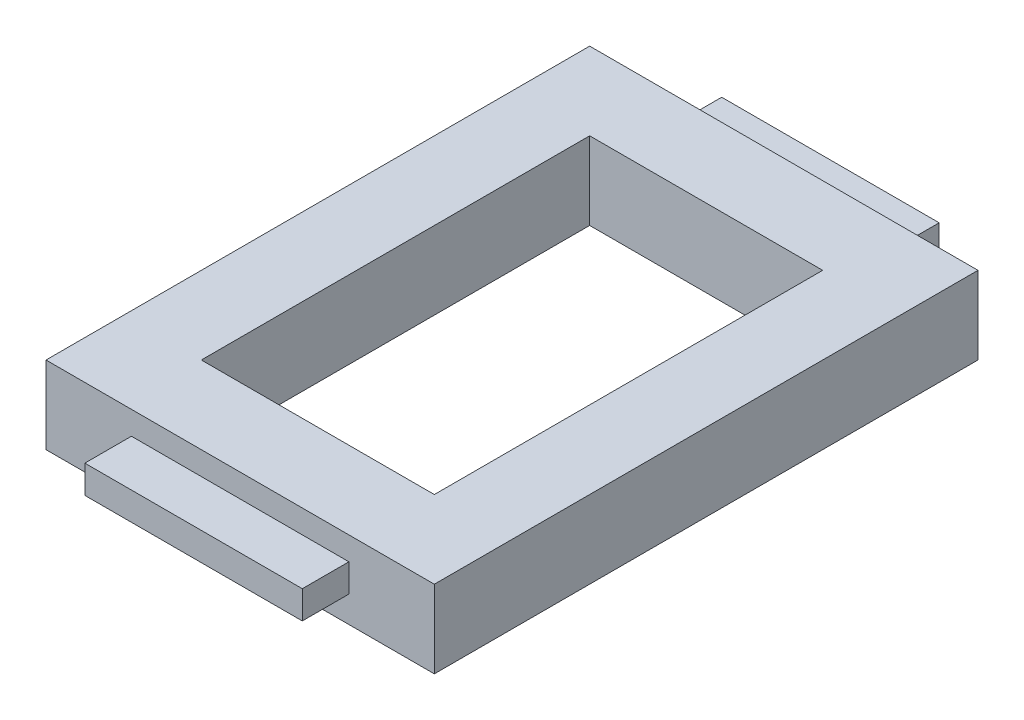
SolidWorks part; units mm, degrees
ref_plane "Front Plane" through (0, 0, 0) normal (0, 0, 1) x (1, 0, 0)
ref_plane "Top Plane" through (0, 0, 0) normal (0, 1, 0) x (1, 0, 0)
ref_plane "Right Plane" through (0, 0, 0) normal (1, 0, 0) x (0, 0, -1)
sketch "Sketch1" plane through (0, 0, 0) normal (0, 1, 0) x (1, 0, 0)
  line L1 (0, 0) -> (25, 0)
  line L2 (0, 0) -> (0, 35)
  line L3 (0, 35) -> (25, 35)
  line L4 (25, 0) -> (25, 35)
  line L5 (5, 30) -> (20, 30)
  line L6 (5, 30) -> (5, 5)
  line L7 (5, 5) -> (20, 5)
  line L8 (20, 30) -> (20, 5)
  dimension "D1" = 25
  dimension "D2" = 35
  dimension "D3" = 5
  dimension "D4" = 5
  dimension "D5" = 5
  dimension "D6" = 5
extrude "Boss-Extrude1" add sketch "Sketch1" along normal blind 5
sketch "Sketch2" plane through (0, 0, 0) normal (0, 0, 1) x (1, 0, 0)
  line L0 (0, 5) -> (0, 0) construction
  line L1 (5.5, 3.5) -> (19.5, 3.5)
  line L2 (5.5, 3.5) -> (5.5, 1.7)
  line L3 (5.5, 1.7) -> (19.5, 1.7)
  line L4 (19.5, 3.5) -> (19.5, 1.7)
  line L5 (25, 5) -> (25, 0) construction
  line L7 (0, 0) -> (25, 0) construction
  dimension "D1" = 5.5
  dimension "D2" = 5.5
  dimension "D3" = 1.8
  dimension "D4" = 1.7
extrude "Boss-Extrude2" add sketch "Sketch2" along normal blind 3
sketch "Sketch3" plane through (0, 0, -35) normal (0, 0, -1) x (-1, 0, 0)
  line L0 (-25, 5) -> (-25, 0) construction
  line L1 (-19.5, 3.4) -> (-5.5, 3.4)
  line L2 (-19.5, 3.4) -> (-19.5, 1.6)
  line L3 (-19.5, 1.6) -> (-5.5, 1.6)
  line L4 (-5.5, 3.4) -> (-5.5, 1.6)
  line L5 (0, 5) -> (0, 0) construction
  line L6 (-25, 0) -> (0, 0) construction
  dimension "D1" = 5.5
  dimension "D2" = 5.5
  dimension "D3" = 1.6
  dimension "D4" = 1.8
extrude "Boss-Extrude3" add sketch "Sketch3" along normal blind 3
